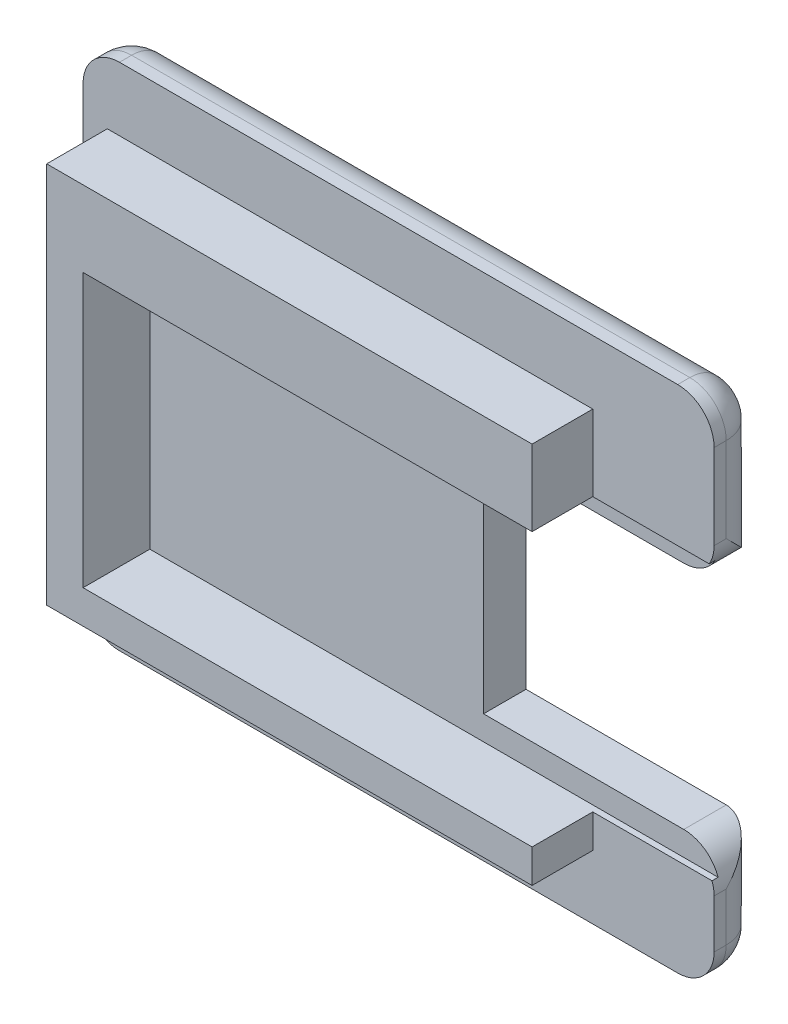
SolidWorks part; units mm, degrees
material "Plain Carbon Steel"
ref_plane "Front Plane" through (0, 0, 0) normal (0, 0, 1) x (1, 0, 0)
ref_plane "Top Plane" through (0, 0, 0) normal (0, 1, 0) x (1, 0, 0)
ref_plane "Right Plane" through (0, 0, 0) normal (1, 0, 0) x (0, 0, -1)
sketch "Sketch1" plane through (0, 0, 0) normal (0, 0, 1) x (1, 0, 0)
  line L1 (-26, 21) -> (26, 21)
  line L2 (-26, 21) -> (-26, -21)
  line L3 (-26, -21) -> (26, -21)
  line L4 (26, 21) -> (26, -21)
  line L5 (-26, 21) -> (26, -21) construction
  line L6 (-26, -21) -> (26, 21) construction
  point P0 (0, 0)
  dimension "D1" = 42
  dimension "D2" = 52
extrude "Boss-Extrude1" add sketch "Sketch1" along normal blind 4
sketch "Sketch2" plane through (0, 0, 4) normal (0, 0, 1) x (1, 0, 0)
  line L0 (26, 21) -> (-26, 21) construction
  line L1 (-24, 15.75) -> (16, 15.75)
  line L2 (-24, 15.75) -> (-24, -15.75)
  line L3 (-24, -15.75) -> (16, -15.75)
  line L4 (16, 15.75) -> (16, -15.75)
  line L5 (-24, 15.75) -> (16, -15.75) construction
  line L6 (-24, -15.75) -> (16, 15.75) construction
  line L7 (-26, -21) -> (26, -21) construction
  line L8 (26, -21) -> (26, 21) construction
  dimension "D1" = 10
  dimension "D2" = 40
  dimension "D3" = 5.25
  dimension "5" = 5.25
extrude "Boss-Extrude2" add sketch "Sketch2" along normal blind 5
sketch "Sketch4" plane through (0, 0, 9) normal (0, 0, 1) x (1, 0, 0)
  line L0 (-26, 21) -> (-26, -21) construction
  line L1 (-21, 9.5) -> (29, 9.5)
  line L2 (-21, 9.5) -> (-21, -13)
  line L3 (-21, -13) -> (29, -13)
  line L4 (29, 9.5) -> (29, -13)
  line L5 (-21, 9.5) -> (29, -13) construction
  line L6 (-21, -13) -> (29, 9.5) construction
  line L8 (-26, -21) -> (26, -21) construction
  line L11 (26, 21) -> (-26, 21) construction
  point P0 (0, 0)
  dimension "D1" = 11.5
  dimension "D2" = 5
  dimension "D3" = 8
  dimension "D4" = 50
extrude "Cut-Extrude2" cut sketch "Sketch4" against normal blind 5.5
sketch "Sketch5" plane through (0, 0, 3.5) normal (0, 0, 1) x (1, 0, 0)
  line L1 (6.5, 8) -> (26, 8)
  line L2 (6.5, 8) -> (6.5, -11)
  line L3 (6.5, -11) -> (26, -11)
  line L4 (26, 8) -> (26, -11)
  line L5 (6.5, 8) -> (26, -11) construction
  line L6 (6.5, -11) -> (26, 8) construction
  line L7 (16, 9.5) -> (-21, 9.5) construction
  line L8 (-21, -13) -> (26, -13) construction
  line L9 (26, -13) -> (26, 9.5) construction
  point P0 (14.4273, 2.716)
  dimension "D1" = 19
  dimension "D2" = 19.5
  dimension "D3" = 1.5
  dimension "D4" = 2
extrude "Cut-Extrude3" cut sketch "Sketch5" against normal blind 10
fillet "Fillet2" radius 3 11 edges at (26, -16, 0) (26, 14.5, 0) (26, 8, 1.75) (26, -11, 1.75) (26, -21, 2) (-26, -21, 2) (0, -21, 0) (-26, 0, 0) (0, 21, 0) (-26, 21, 2) (26, 21, 2)
